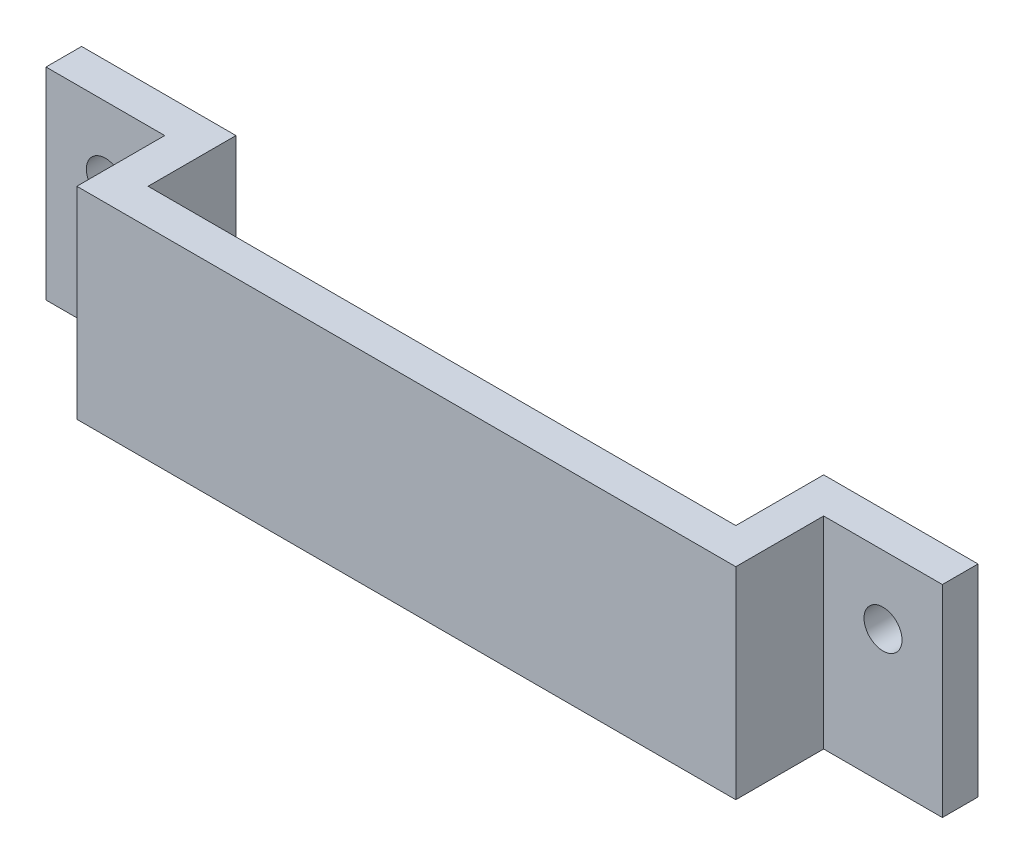
SolidWorks part; units mm, degrees
ref_plane "Plano frontal" through (0, 0, 0) normal (0, 0, 1) x (1, 0, 0)
ref_plane "Plano superior" through (0, 0, 0) normal (0, 1, 0) x (1, 0, 0)
ref_plane "Plano direito" through (0, 0, 0) normal (1, 0, 0) x (0, 0, -1)
sketch "Esboço1" plane through (0, 0, 0) normal (0, 0, 1) x (1, 0, 0)
  line L1 (-27.75, 8.5) -> (27.75, 8.5)
  line L2 (-27.75, 8.5) -> (-27.75, -8.5)
  line L3 (-27.75, -8.5) -> (27.75, -8.5)
  line L4 (27.75, 8.5) -> (27.75, -8.5)
  line L5 (0, -8.5) -> (0, 8.5) construction
  line L6 (-27.75, 0) -> (27.75, 0) construction
  point P4 (0, 0)
  point P152 (0, 0)
  dimension "D1" = 17
  dimension "D2" = 55.5
extrude "Ressalto-extrusão1" add sketch "Esboço1" along normal blind 3
sketch "Esboço9" plane through (0, 0, 0) normal (0, 0, -1) x (-1, 0, 0)
  line L5 (27.75, -8.5) -> (-27.75, -8.5) construction
  line L6 (-27.75, 8.5) -> (-24.75, 8.5)
  line L7 (0, 0) -> (0, 50000) construction
  line L8 (-27.75, 8.5) -> (-27.75, -8.5)
  line L17 (-27.75, -8.5) -> (-24.75, -8.5)
  line L18 (-24.75, 8.5) -> (-24.75, -8.5)
  line L19 (-26.25, -8.5) -> (-26.25, 8.5) construction
  line L20 (-27.75, 0) -> (-24.75, 0) construction
  line L21 (27.75, 0) -> (24.75, 0) construction
  line L22 (26.25, -8.5) -> (26.25, 8.5) construction
  line L23 (24.75, 8.5) -> (24.75, -8.5)
  line L24 (27.75, -8.5) -> (24.75, -8.5)
  line L25 (27.75, 8.5) -> (27.75, -8.5)
  line L26 (27.75, 8.5) -> (24.75, 8.5)
  point P16 (26.25, 0)
  point P276 (-26.25, 0)
  dimension "D1" = 3
extrude "Ressalto-extrusão5" add sketch "Esboço9" along normal blind 7.4
sketch "Esboço10" plane through (0, 8.5, 0) normal (0, 1, 0) x (1, 0, 0)
  line L1 (27.75, 7.4) -> (37.75, 7.4)
  line L2 (27.75, 7.4) -> (27.75, 4.4)
  line L3 (27.75, 4.4) -> (37.75, 4.4)
  line L4 (37.75, 7.4) -> (37.75, 4.4)
  line L5 (32.75, 4.4) -> (32.75, 7.4) construction
  line L6 (27.75, 5.9) -> (37.75, 5.9) construction
  line L12 (27.75, -3) -> (-27.75, -3) construction
  line L14 (23.75, -3) -> (41.75, -3) construction
  line L15 (23.75, -3) -> (23.75, 7.4) construction
  line L16 (23.75, 7.4) -> (41.75, 7.4) construction
  line L17 (41.75, -3) -> (41.75, 7.4) construction
  line L18 (32.75, 7.4) -> (32.75, -3) construction
  line L19 (23.75, 2.2) -> (41.75, 2.2) construction
  line L20 (24.75, 7.4) -> (27.75, 7.4) construction
  line L21 (24.75, 7.4) -> (24.75, 0) construction
  line L22 (0, 0) -> (0, -50000) construction
  line L23 (24.75, 0) -> (-24.75, 0) construction
  line L24 (-27.75, 5.9) -> (-37.75, 5.9) construction
  line L25 (-32.75, 4.4) -> (-32.75, 7.4) construction
  line L26 (-37.75, 7.4) -> (-37.75, 4.4)
  line L27 (-27.75, 4.4) -> (-37.75, 4.4)
  line L28 (-27.75, 7.4) -> (-27.75, 4.4)
  line L29 (-27.75, 7.4) -> (-37.75, 7.4)
  point P18 (0, 0)
  point P27 (-32.75, 5.9)
  point P28 (-32.75, 2.2)
  point P84 (32.75, 2.2)
  point P148 (32.75, 5.9)
  dimension "D1" = 3
  dimension "D2" = 1
  dimension "D3" = 18
  dimension "D4" = 4
extrude "Ressalto-extrusão6" add sketch "Esboço10" against normal through all
sketch "Esboço11" plane through (0, 0, -4.4) normal (0, 0, 1) x (1, 0, 0)
  line L0 (-37.75, -8.5) -> (-27.75, -8.5) construction
  line L1 (-41.75, 8.5) -> (-23.75, 8.5) construction
  line L2 (-41.75, 8.5) -> (-41.75, -8.5) construction
  line L3 (-41.75, -8.5) -> (-23.75, -8.5) construction
  line L4 (-23.75, 8.5) -> (-23.75, -8.5) construction
  line L5 (-32.75, -8.5) -> (-32.75, 8.5) construction
  line L6 (-41.75, 0) -> (-23.75, 0) construction
  line L7 (-37.75, 8.5) -> (-27.75, 8.5) construction
  line L8 (-37.75, -8.5) -> (-37.75, 8.5) construction
  line L9 (0, 0) -> (0, 50000) construction
  circle A0 centre (-32.75, 2.75) radius 1.6
  circle A1 centre (32.75, 2.75) radius 1.6
  point P156 (-32.75, 0)
  dimension "D3" = 3.2
  dimension "D1" = 4
  dimension "D2" = 18
  dimension "D4" = 11.25
extrude "Corte-extrusão4" cut sketch "Esboço11" against normal up to next
